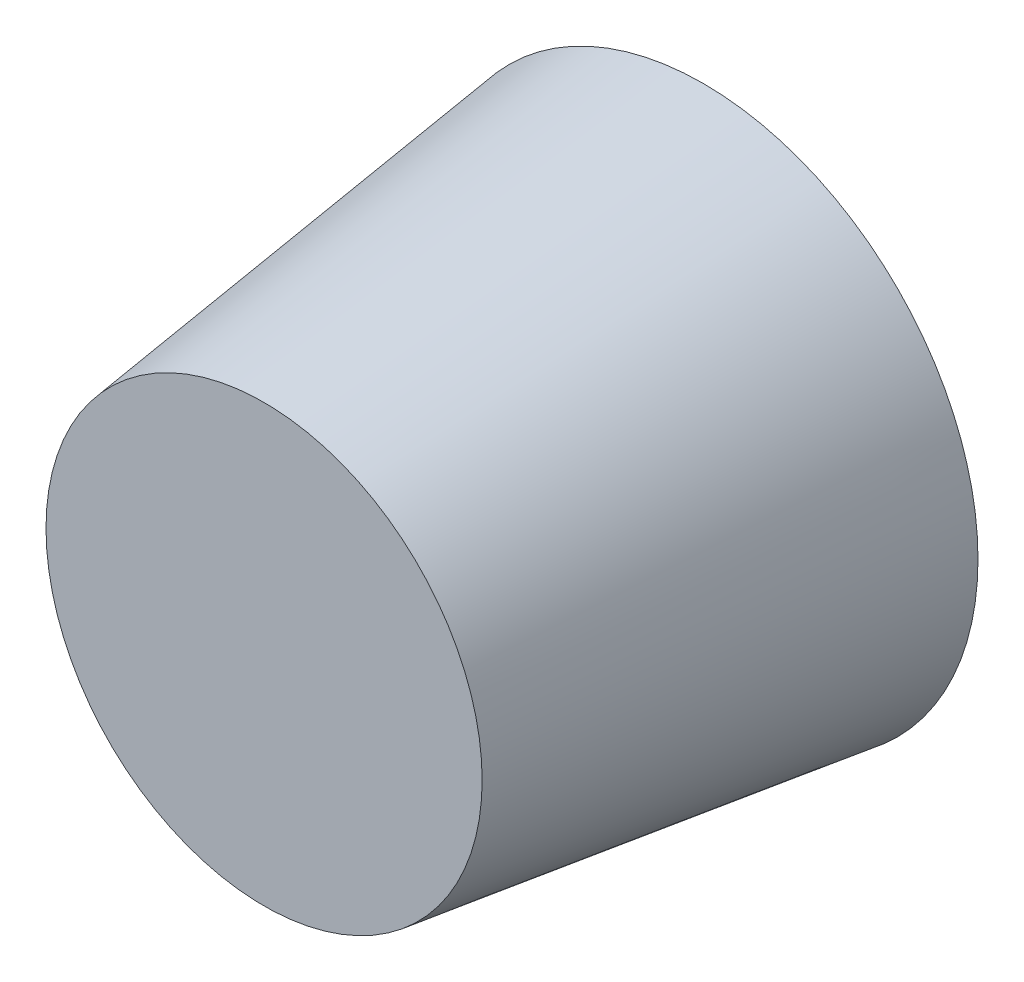
SolidWorks part; units mm, degrees
ref_plane "Alzado" through (0, 0, 0) normal (0, 0, 1) x (1, 0, 0)
ref_plane "Planta" through (0, 0, 0) normal (0, 1, 0) x (1, 0, 0)
ref_plane "Vista lateral" through (0, 0, 0) normal (1, 0, 0) x (0, 0, -1)
sketch "Croquis1" plane through (0, 0, 0) normal (0, 0, 1) x (1, 0, 0)
  circle A0 centre (0, 0) radius 5
  dimension "D1" = 10
extrude "Saliente-Extruir1" add sketch "Croquis1" along normal blind 8
sketch "Croquis2" plane through (0, 0, 8) normal (0, 0, 1) x (1, 0, 0)
  circle A0 centre (0, 0) radius 4
  dimension "D1" = 8
sketch "Croquis3" plane through (0, 0, 0) normal (1, 0, 0) x (0, 0, -1)
  line L0 (-8, 3.971) -> (0, 5)
  line L1 (-8, 4) -> (-8, -4) construction
  line L5 (-8, 0) -> (3.6969, 0) construction
  line L6 (0, 5) -> (-8, 5)
  line L7 (-8, 5) -> (-8, 3.971)
revolve "Cortar-Revolución2" cut sketch "Croquis3" angle 360 about L5
sketch "Croquis4" plane through (0, 0, 0) normal (0, 0, -1) x (-1, 0, 0)
  circle A0 centre (0, 0) radius 2.55
  dimension "D1" = 5.1
extrude "Cortar-Extruir1" cut sketch "Croquis4" against normal blind 4
